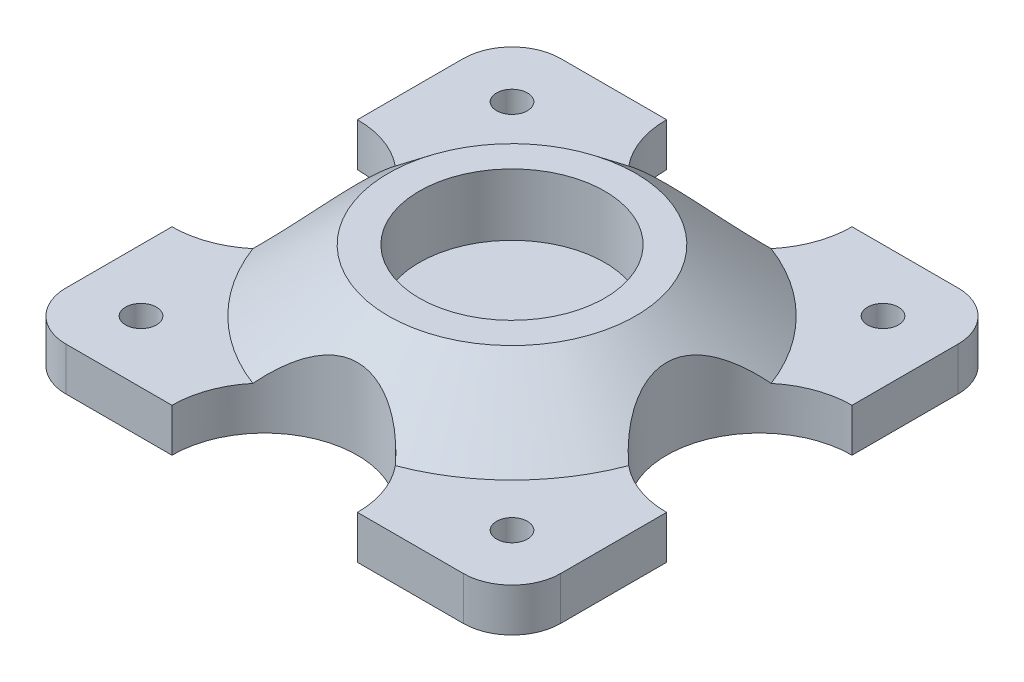
SolidWorks part; units mm, degrees
ref_plane "Front Plane" through (0, 0, 0) normal (0, 0, 1) x (1, 0, 0)
ref_plane "Top Plane" through (0, 0, 0) normal (0, 1, 0) x (1, 0, 0)
ref_plane "Right Plane" through (0, 0, 0) normal (1, 0, 0) x (0, 0, -1)
sketch "Sketch1" plane through (0, 0, 0) normal (0, 1, 0) x (1, 0, 0)
  line L1 (-40.8, 50.8) -> (40.8, 50.8)
  line L2 (-50.8, 40.8) -> (-50.8, -40.8)
  line L3 (-40.8, -50.8) -> (40.8, -50.8)
  line L4 (50.8, 40.8) -> (50.8, -40.8)
  line L5 (-50.8, 50.8) -> (50.8, -50.8) construction
  line L6 (-50.8, -50.8) -> (50.8, 50.8) construction
  arc A0 (40.8, -50.8) -> (50.8, -40.8) centre (40.8, -40.8) ccw
  arc A1 (-40.8, -50.8) -> (-50.8, -40.8) centre (-40.8, -40.8) cw
  arc A2 (50.8, 40.8) -> (40.8, 50.8) centre (40.8, 40.8) ccw
  arc A3 (-40.8, 50.8) -> (-50.8, 40.8) centre (-40.8, 40.8) ccw
  point P0 (0, 0)
  dimension "D2" = 10
  dimension "D1" = 101.6
extrude "Boss-Extrude1" add sketch "Sketch1" along normal blind 8.89
sketch "Sketch2" plane through (0, 0, 0) normal (0, 0, 1) x (1, 0, 0)
  line L0 (0, 8.89) -> (0, 21.59)
  line L1 (40.8, 8.89) -> (-40.8, 8.89) construction
  line L2 (0, 21.59) -> (-25.4, 21.59)
  line L3 (-25.4, 21.59) -> (-41.28, 8.89)
  line L4 (-41.28, 8.89) -> (0, 8.89)
  line L5 (40.8, 0) -> (-40.8, 0) construction
  dimension "D1" = 21.59
  dimension "D2" = 25.4
  dimension "D3" = 41.28
revolve "Revolve1" add sketch "Sketch2" angle 360 about L0
sketch "Sketch3" plane through (0, 21.59, 0) normal (0, 1, 0) x (1, 0, 0)
  line L0 (-50.8, 40.8) -> (-50.8, -40.8) construction
  line L1 (-40.8, -50.8) -> (40.8, -50.8) construction
  line L2 (50.8, -40.8) -> (50.8, 40.8) construction
  line L3 (40.8, 50.8) -> (-40.8, 50.8) construction
  line L4 (-50.8, -19.05) -> (-50.8, 19.05)
  line L5 (-38.1, -38.1) -> (38.1, -38.1) construction
  line L6 (-38.1, -38.1) -> (-38.1, 38.1) construction
  line L7 (-38.1, 38.1) -> (38.1, 38.1) construction
  line L8 (38.1, -38.1) -> (38.1, 38.1) construction
  line L9 (-38.1, -38.1) -> (38.1, 38.1) construction
  line L10 (-38.1, 38.1) -> (38.1, -38.1) construction
  line L11 (-19.05, -50.8) -> (19.05, -50.8)
  line L12 (50.8, -19.05) -> (50.8, 19.05)
  line L13 (-19.05, 50.8) -> (19.05, 50.8)
  circle A0 centre (0, 0) radius 19.05
  arc A1 (-50.8, -19.05) -> (-50.8, 19.05) centre (-50.8, 0) ccw
  arc A2 (19.05, -50.8) -> (-19.05, -50.8) centre (0, -50.8) ccw
  arc A3 (50.8, 19.05) -> (50.8, -19.05) centre (50.8, 0) ccw
  arc A4 (-19.05, 50.8) -> (19.05, 50.8) centre (0, 50.8) ccw
  circle A5 centre (-38.1, -38.1) radius 3.175
  circle A6 centre (-38.1, 38.1) radius 3.175
  circle A7 centre (38.1, 38.1) radius 3.175
  circle A8 centre (38.1, -38.1) radius 3.175
  dimension "D1" = 38.1
  dimension "D4" = 6.35
  dimension "D2" = 76.2
  dimension "D3" = 76.2
extrude "Cut-Extrude2" cut sketch "Sketch3" against normal through all
sketch "Sketch4" plane through (0, 0, 0) normal (0, -1, 0) x (1, 0, 0)
  circle A0 centre (0, 0) radius 19.05 construction
  circle A1 centre (0, 0) radius 19.05
  circle A2 centre (0, 0) radius 19.05
  circle A3 centre (0, 0) radius 19.05
  dimension "D1" = 0
sketch "Sketch5" plane through (0, 0, 0) normal (0, -1, 0) x (1, 0, 0)
  circle A0 centre (0, 0) radius 19.05 construction
  circle A1 centre (0, 0) radius 19.05
sketch "Sketch6" plane through (0, 0, 0) normal (0, -1, 0) x (1, 0, 0)
  circle A0 centre (0, 0) radius 19.05 construction
  circle A1 centre (0, 0) radius 19.05
extrude "Boss-Extrude2" add sketch "Sketch6" against normal up to surface (8.89 mm away) up to face at (38.1, 8.89, -34.925)
